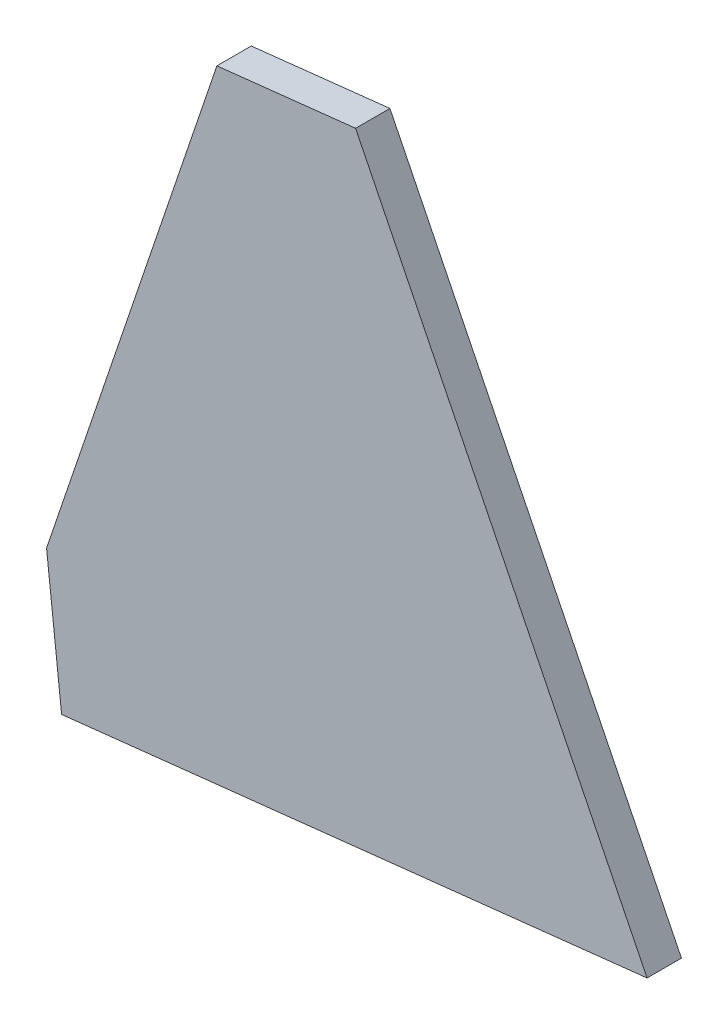
SolidWorks part; units mm, degrees
ref_plane "Plan de face" through (0, 0, 0) normal (0, 0, 1) x (1, 0, 0)
ref_plane "Plan de dessus" through (0, 0, 0) normal (0, 1, 0) x (1, 0, 0)
ref_plane "Plan de droite" through (0, 0, 0) normal (1, 0, 0) x (0, 0, -1)
sketch "Esquisse1" plane through (0, 0, 0) normal (0, 0, 1) x (1, 0, 0)
  line L0 (-66.4814, -169.2476) -> (103.9445, -150.4692)
  line L1 (103.9445, -150.4692) -> (19.0901, 21.3128)
  line L2 (19.0901, 21.3128) -> (-21.2826, 16.8644)
  line L3 (-21.2826, 16.8644) -> (-70.8623, -129.4883)
  line L4 (-70.8623, -129.4883) -> (-66.4814, -169.2476)
  line L5 (-317.2933, -196.8834) -> (-33.1193, -165.5716) construction
  line L6 (243.1874, -432.3571) -> (19.0901, 21.3128) construction
  line L7 (12.2023, 532.9596) -> (-30.4895, -125.0398) construction
  line L8 (-30.4895, -125.0398) -> (-328.6848, -157.8965) construction
  dimension "D1" = 40
extrude "Boss.-Extru.1" add sketch "Esquisse1" along normal blind 10
